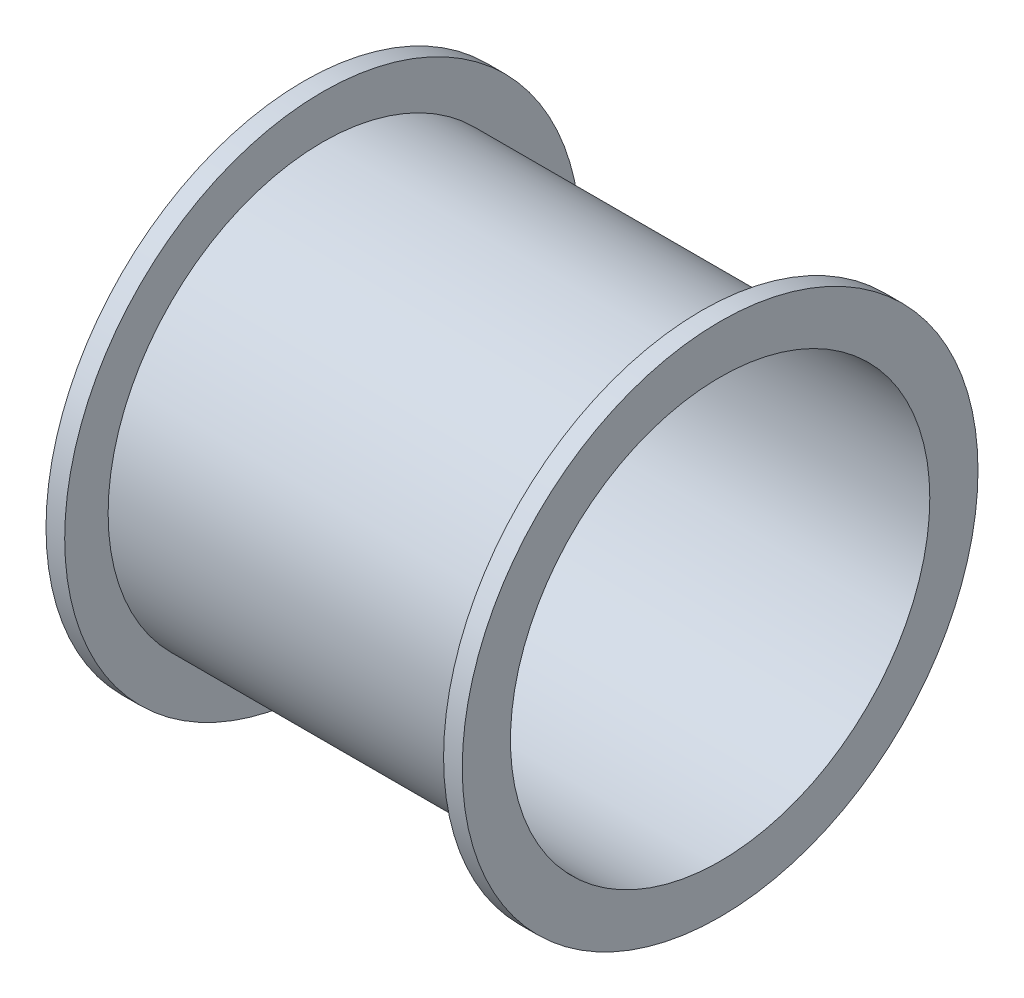
SolidWorks part; units mm, degrees
ref_plane "Front Plane" through (0, 0, 0) normal (0, 0, 1) x (1, 0, 0)
ref_plane "Top Plane" through (0, 0, 0) normal (0, 1, 0) x (1, 0, 0)
ref_plane "Right Plane" through (0, 0, 0) normal (1, 0, 0) x (0, 0, -1)
sketch "Helix_Circles" plane through (0, 0, 0) normal (1, 0, 0) x (0, 0, -1)
  circle A0 centre (0, 0) radius 57
  circle A1 centre (0, 0) radius 58.3
  dimension "D1" = 114
  dimension "D2" = 1.3
sketch "Sketch17" plane through (0, 0, 0) normal (1, 0, 0) x (0, 0, -1)
  circle A0 centre (0, 0) radius 60.575
  dimension "D1" = 121.15
sketch "Sketch25" plane through (0, 0, 0) normal (1, 0, 0) x (0, 0, -1)
  circle A0 centre (0, 0) radius 62.9585
  dimension "D1" = 125.917
sketch "Sketch32" plane through (0, 0, 0) normal (1, 0, 0) x (0, 0, -1)
  circle A0 centre (0, 0) radius 65.3415
  dimension "D1" = 130.683
sketch "Sketch43" plane through (0, 0, 0) normal (1, 0, 0) x (0, 0, -1)
  circle A0 centre (0, 0) radius 67.725
  dimension "D1" = 135.45
sketch "Sketch50" plane through (0, 0, 0) normal (1, 0, 0) x (0, 0, -1)
  circle A0 centre (0, 0) radius 70.1085
  dimension "D1" = 140.217
extrude "Boss-Extrude1" add sketch "Helix_Circles" along normal blind 103
extrude "Boss-Extrude2" add sketch "Sketch50" against normal blind 5.08
ref_plane "Plane2" through (103, 0, 0) normal (1, 0, 0) x (0, 0, -1)
sketch "Sketch58" plane through (103, 0, 0) normal (1, 0, 0) x (0, 0, -1)
  circle A0 centre (0, 0) radius 57
  circle A1 centre (0, 0) radius 70.104
  dimension "D1" = 140.208
extrude "Boss-Extrude6" add sketch "Sketch58" along normal blind 5.08
ref_plane "Plane3" through (0, 0, 0) normal (1, 0, 0) x (0, 0, -1)
sketch "Sketch59" plane through (0, 0, 0) normal (1, 0, 0) x (0, 0, -1)
  circle A2 centre (-25.3802, 0) radius 17.2358
  circle A3 centre (25.3802, 0) radius 17.2358
extrude "Boss-Extrude7" add sketch "Sketch59" along normal blind 7.62
